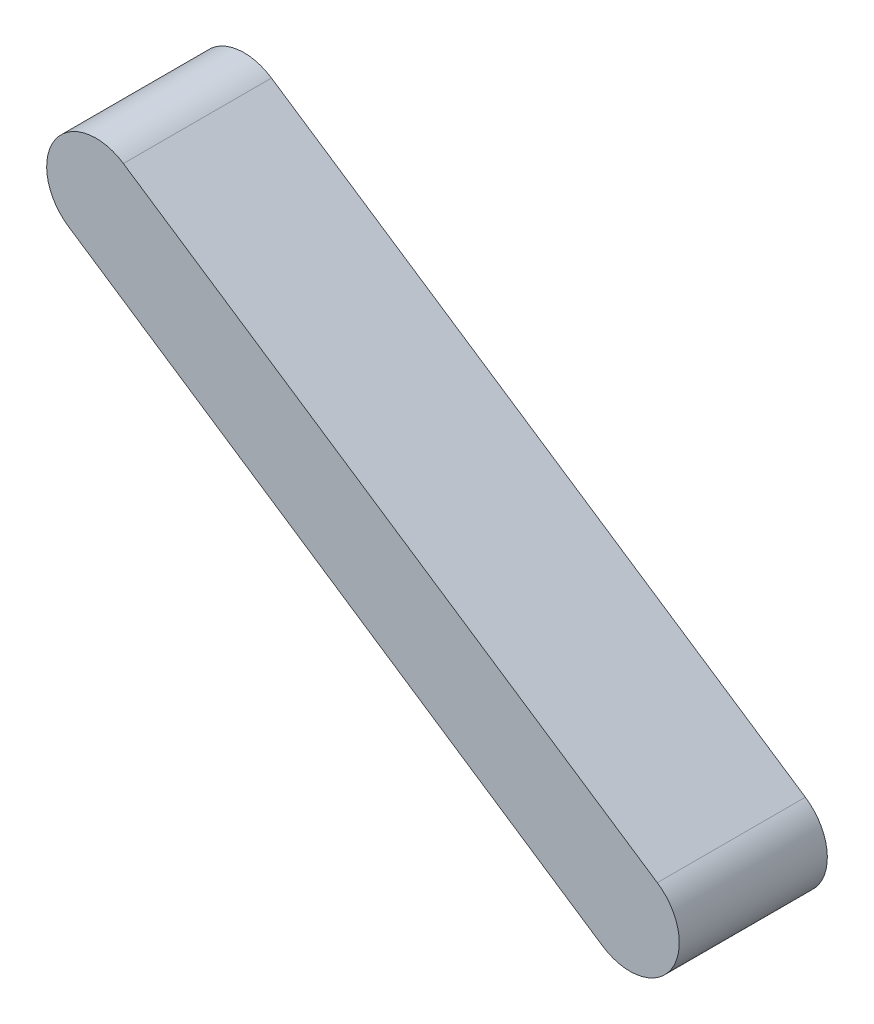
SolidWorks part; units mm, degrees
ref_plane "前视基准面" through (0, 0, 0) normal (0, 0, 1) x (1, 0, 0)
ref_plane "上视基准面" through (0, 0, 0) normal (0, 1, 0) x (1, 0, 0)
ref_plane "右视基准面" through (0, 0, 0) normal (1, 0, 0) x (0, 0, -1)
sketch "草图2" plane through (0, 0, 0) normal (0, 0, 1) x (1, 0, 0)
  line L0 (0, 0) -> (-108.1722, 72.1025) construction
  line L1 (-5.5463, -8.3209) -> (-113.7186, 63.7816)
  line L2 (5.5463, 8.3209) -> (-102.6259, 80.4235)
  arc A0 (-5.5463, -8.3209) -> (5.5463, 8.3209) centre (0, 0) ccw
  arc A1 (-102.6259, 80.4235) -> (-113.7186, 63.7816) centre (-108.1722, 72.1025) ccw
  point P2 (-54.0861, 36.0513)
  dimension "D1" = 130
  dimension "D2" = 20
extrude "凸台-拉伸1" add sketch "草图2" along normal mid plane 30 contours L1 A1 L2 A0
